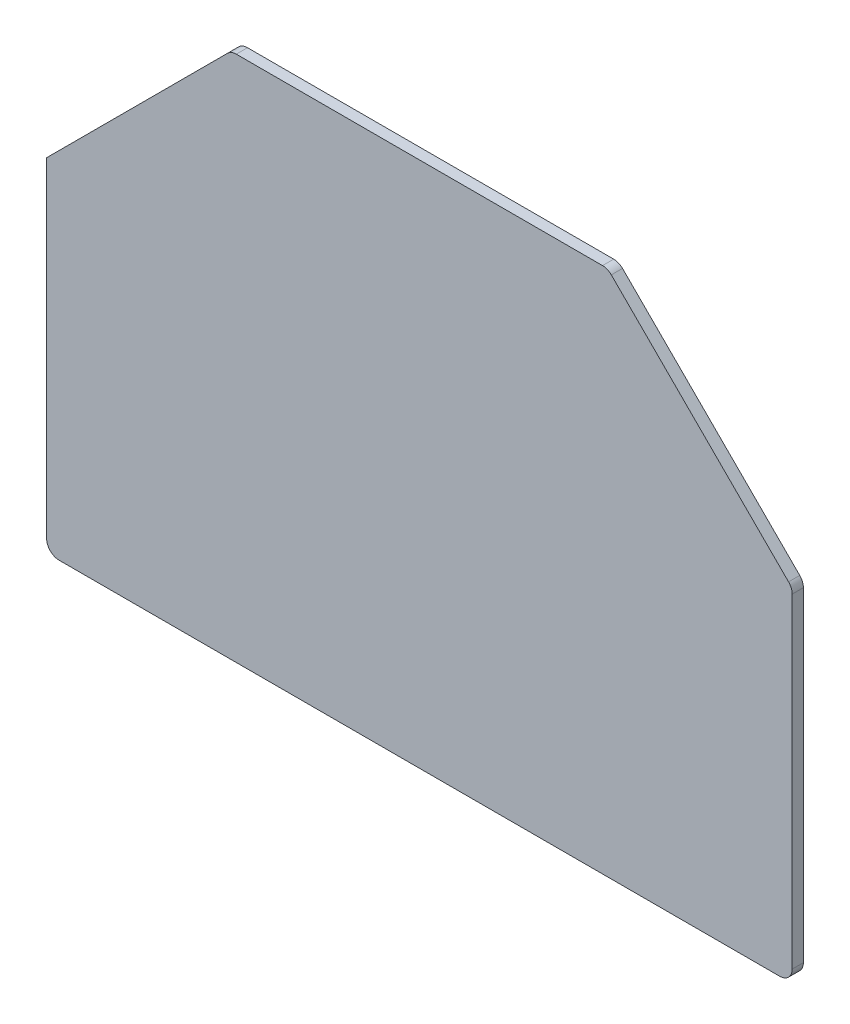
SolidWorks part; units mm, degrees
material "Acrylic (Medium-high impact)"
ref_plane "Front Plane" through (0, 0, 0) normal (0, 0, 1) x (1, 0, 0)
ref_plane "Top Plane" through (0, 0, 0) normal (0, 1, 0) x (1, 0, 0)
ref_plane "Right Plane" through (0, 0, 0) normal (1, 0, 0) x (0, 0, -1)
sketch "Sketch1" plane through (0, 0, 0) normal (0, 0, 1) x (1, 0, 0)
  line L0 (0, 137.7538) -> (74.2462, 212)
  line L1 (0, 0) -> (300, 0)
  line L2 (0, 0) -> (0, 137.7538)
  line L3 (74.2462, 212) -> (225.7538, 212)
  line L4 (300, 0) -> (300, 137.7538)
  line L5 (225.7538, 212) -> (300, 137.7538)
  dimension "D1" = 300
  dimension "D2" = 212
  dimension "D3" = 135
  dimension "D4" = 135
  dimension "D5" = 105
  dimension "D6" = 105
extrude "Boss-Extrude1" add sketch "Sketch1" along normal blind 4.5
fillet "Fillet1" radius 5 5 edges at (0, 0, 2.25) (300, 0, 2.25) (300, 137.7538, 2.25) (225.7538, 212, 2.25) (74.2462, 212, 2.25)
